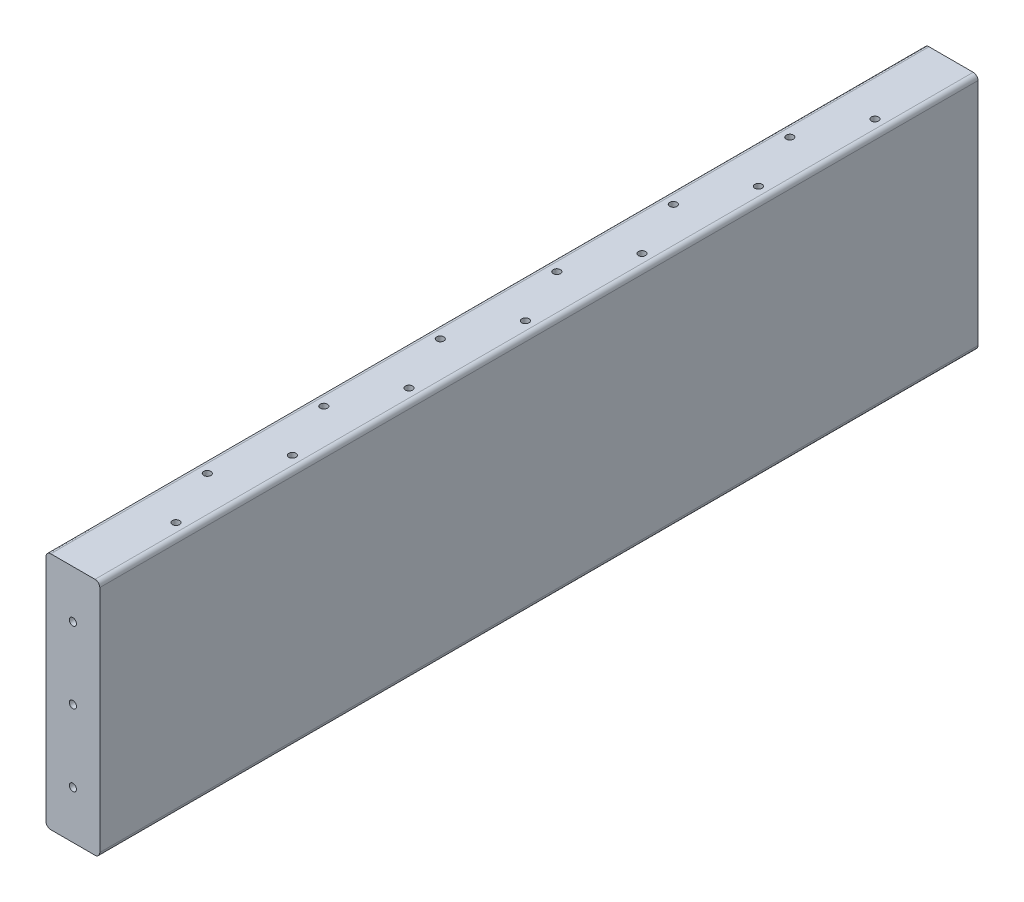
SolidWorks part; units mm, degrees
material "Beech"
ref_plane "Front Plane" through (0, 0, 0) normal (0, 0, 1) x (1, 0, 0)
ref_plane "Top Plane" through (0, 0, 0) normal (0, 1, 0) x (1, 0, 0)
ref_plane "Right Plane" through (0, 0, 0) normal (1, 0, 0) x (0, 0, -1)
sketch "Sketch1" plane through (0, 0, 0) normal (0, 0, 1) x (1, 0, 0)
  line L0 (-31.1883, 134.2727) -> (-31.1883, -65.7273)
  line L1 (-31.1883, -65.7273) -> (13.8117, -65.7273)
  line L2 (-31.1883, 134.2727) -> (13.8117, 134.2727)
  line L3 (13.8117, 134.2727) -> (13.8117, -65.7273)
extrude "Boss-Extrude1" add sketch "Sketch1" along normal blind 735
fillet "Fillet1" radius 4 4 edges at (-31.1883, -65.7273, 367.5) (13.8117, -65.7273, 367.5) (-31.1883, 134.2727, 367.5) (13.8117, 134.2727, 367.5)
hole_wizard "Ø6.0mm Dowel Slot1" positions "Sketch2" profile "Sketch3" size "Ø6.0" standard "ISO" slot yes
sketch "Sketch2" plane through (863.8117, -65.7273, 780) normal (0, 0, 1) x (1, 0, 0)
  point P0 (-872.5, 160)
  point P2 (-872.5, 100)
  point P4 (-872.5, 40)
sketch "Sketch3" plane through (-8.6883, 94.2727, 780) normal (1, 0, 0) x (0, -1, 0)
  line L0 (0, 0) -> (0, 65)
  line L1 (0, 65) -> (3, 63.1974)
  line L2 (3, 63.1974) -> (3, 0.025)
  line L3 (3, 0.025) -> (3.025, 0)
  line L4 (3.025, 0) -> (0, 0)
  line L5 (-3, 0.025) -> (-3.025, 0) construction
  line L6 (0, 65) -> (-3, 63.1974) construction
  line L7 (0, -6.35) -> (0, 107.95) construction
  dimension "Hole Dia." = 6
  dimension "Hole Depth" = 65
  dimension "Near C'Sink Dia." = 6.05
  dimension "Near C'Sink Angle" = 90
  dimension "Drill Angle" = 118
hole_wizard "Ø6.0mm Dowel Slot2" positions "Sketch4" profile "Sketch5" size "Ø6.0" standard "ISO" slot yes
sketch "Sketch4" plane through (863.8117, -65.7273, -45) normal (0, 0, -1) x (-1, 0, 0)
  point P0 (872.5, 160)
  point P2 (872.5, 100)
  point P4 (872.5, 40)
sketch "Sketch5" plane through (-8.6883, 94.2727, -45) normal (1, 0, 0) x (0, 1, 0)
  line L0 (0, 0) -> (0, 65)
  line L1 (0, 65) -> (3, 63.1974)
  line L2 (3, 63.1974) -> (3, 0.025)
  line L3 (3, 0.025) -> (3.025, 0)
  line L4 (3.025, 0) -> (0, 0)
  line L5 (-3, 0.025) -> (-3.025, 0) construction
  line L6 (0, 65) -> (-3, 63.1974) construction
  line L7 (0, -6.35) -> (0, 107.95) construction
  dimension "Hole Dia." = 6
  dimension "Hole Depth" = 65
  dimension "Near C'Sink Dia." = 6.05
  dimension "Near C'Sink Angle" = 90
  dimension "Drill Angle" = 118
hole_wizard "Ø6.0mm Dowel Slot3" [suppressed] positions "Sketch6" profile "Sketch7" size "Ø6.0" standard "ISO"
sketch "Sketch6" plane through (-971.1883, 146.2727, -45) normal (0, 1, 0) x (0, 0, 1)
  point P0 (22.5608, 973.75)
  point P3 (22.5608, 951.25)
  point P6 (802.5608, 973.75)
  point P9 (802.5608, 951.25)
  point P12 (120.3608, 951.25)
  point P16 (71.3108, 973.75)
  point P20 (169.1108, 973.75)
  point P22 (218.1608, 951.25)
  point P24 (266.9108, 973.75)
  point P26 (315.9608, 951.25)
  point P28 (364.7108, 973.75)
  point P30 (413.7608, 951.25)
  point P32 (462.5108, 973.75)
  point P34 (511.5608, 951.25)
  point P36 (560.3108, 973.75)
  point P41 (609.3608, 951.25)
  point P43 (658.1108, 973.75)
  point P45 (707.1608, 951.25)
  point P50 (755.9108, 973.75)
sketch "Sketch7" plane through (2.5617, 146.2727, -22.4392) normal (1, 0, 0) x (0, 0, 1)
  line L0 (0, 0) -> (0, 30)
  line L1 (0, 30) -> (3, 28.1974)
  line L2 (3, 28.1974) -> (3, 0)
  line L3 (3, 0) -> (0, 0)
  line L4 (0, 30) -> (-3, 28.1974) construction
  line L5 (0, -6.35) -> (0, 107.95) construction
  dimension "Hole Dia." = 6
  dimension "Hole Depth" = 30
  dimension "Drill Angle" = 118
ref_plane "Plane1" through (0, 34.2727, 0) normal (0, 1, 0) x (1, 0, 0)
mirror "Mirror1" [suppressed] about plane through (0, 34.2727, 0) normal (0, 1, 0)
hole_wizard "Ø6.0mm Dowel Slot4" positions "Sketch8" profile "Sketch9" size "Ø6.0" standard "ISO"
sketch "Sketch8" plane through (863.8117, 146.2727, -45) normal (0, 1, 0) x (0, 0, 1)
  point P0 (22.5608, -1722.5)
  point P3 (120.5996, -1722.5)
  point P7 (217.974, -1722.5)
  point P9 (314.7913, -1722.5)
  point P11 (412.5608, -1722.5)
  point P13 (510.3116, -1722.5)
  point P15 (607.5219, -1722.5)
  point P17 (704.9775, -1722.5)
  point P19 (802.5608, -1722.5)
  point P22 (802.5608, -1458.5)
  point P26 (802.5608, -1546.5)
  point P28 (802.5608, -1634.5)
  point P30 (22.5608, -1546.5)
  point P34 (22.5608, -1458.5)
  point P36 (22.5608, -1634.5)
  point P38 (22.5608, -932.5)
  point P41 (-22.4962, -917.6022)
  point P44 (71.2428, -861.25)
  point P48 (120.5996, -883.75)
  point P52 (169.2328, -861.25)
  point P54 (217.974, -883.75)
  point P56 (268.0506, -861.25)
  point P58 (314.7913, -883.75)
  point P60 (364.7201, -861.25)
  point P62 (414.2928, -883.75)
  point P64 (462.5664, -861.25)
  point P66 (511.551, -883.75)
  point P68 (560.2153, -861.25)
  point P70 (657.9263, -861.25)
  point P72 (609.5282, -883.75)
  point P74 (707.1553, -883.75)
  point P76 (755.5069, -861.25)
  point P78 (802.5608, -932.5)
  point P80 (847.4962, -917.6022)
  point P83 (927.0078, -850.8784)
  point P86 (1006.7507, -783.9604)
  point P90 (1086.3394, -717.1719)
  point P93 (802.5608, -761.25)
  point P96 (802.5608, -664.25)
  point P99 (1166.0052, -650.3187)
  point P102 (1185.001, -609.0604)
  point P105 (1185.001, -511.1051)
  point P109 (1185.001, -409.0604)
  point P112 (1185.001, -309.1708)
  point P114 (1185.001, -209.0363)
  point P116 (1185.001, -109.0604)
  point P119 (1185.001, -9.0604)
  point P122 (1021.9151, 22.5)
  point P125 (1024.5, 67.5)
  point P128 (1133.73, 67.5)
  point P131 (1133.73, 22.5)
  point P134 (913.5, 67.5)
  point P137 (910.7185, 22.5)
  point P141 (802.5, 67.5)
  point P147 (802.5, 22.5)
  point P149 (688.5, 67.5)
  point P152 (688.5, 22.5)
  point P154 (577.5192, 67.5)
  point P156 (577.9151, 22.5)
  point P159 (466.3273, 67.5)
  point P161 (466.3273, 22.5)
  point P163 (355.5, 67.5)
  point P166 (355.9151, 22.5)
  point P169 (244.5, 67.5)
  point P172 (244.5, 22.5)
  point P174 (133.5309, 67.5)
  point P176 (133.5309, 22.5)
  point P178 (22.5608, 67.5)
  point P180 (22.5608, 22.5)
  point P182 (-87.7299, 67.5)
  point P184 (-88.0849, 22.5)
  point P187 (-199.0849, 67.5)
  point P190 (-199.0849, 22.5)
  point P193 (-310.0849, 22.5)
  point P196 (-310.0849, 67.5)
  point P199 (-341.0052, -650.3187)
  point P202 (-261.3394, -717.1719)
  point P205 (-181.7507, -783.9604)
  point P209 (-102.0078, -850.8784)
  point P211 (22.5608, -77.5)
  point P214 (22.5608, -179.25)
  point P217 (22.5608, -275.9132)
  point P219 (22.5608, -373.0681)
  point P221 (22.5608, -469.6127)
  point P223 (22.5608, -567.3178)
  point P225 (22.5608, -664.25)
  point P228 (22.5608, -761.25)
  point P231 (802.5608, 167.5)
  point P234 (1185.001, 190.9134)
  point P236 (1185.001, 90.9396)
  point P239 (1185.001, 290.9396)
  point P242 (1185.001, 390.9396)
  point P245 (1185.001, 491.2681)
  point P247 (1185.001, 590.9396)
  point P250 (1185.001, 699.7184)
  point P253 (1166.0052, 740.3187)
  point P256 (1086.3394, 807.1719)
  point P259 (1006.7507, 873.9604)
  point P263 (927.0078, 940.8784)
  point P266 (847.4962, 1007.6022)
  point P269 (802.5608, 1022.8195)
  point P271 (802.5608, 973.75)
  point P274 (802.5608, 951.25)
  point P277 (755.5069, 973.75)
  point P281 (802.5608, 852.5)
  point P284 (707.1553, 951.25)
  point P288 (657.9263, 973.75)
  point P290 (609.5282, 951.25)
  point P292 (560.2153, 973.75)
  point P294 (511.5608, 951.25)
  point P297 (462.5664, 973.75)
  point P299 (412.5608, 951.25)
  point P301 (364.7108, 973.75)
  point P304 (315.9608, 951.25)
  point P307 (266.9108, 973.75)
  point P310 (218.1608, 951.25)
  point P313 (169.1108, 973.75)
  point P316 (120.3608, 951.25)
  point P319 (71.3108, 973.75)
  point P322 (22.5608, 973.75)
  point P325 (22.5608, 1022.5)
  point P328 (22.5608, 951.25)
  point P331 (-102.0078, 940.8784)
  point P334 (-181.7507, 873.9604)
  point P338 (-22.4962, 1007.6022)
  point P341 (-261.3394, 807.1719)
  point P343 (-341.0052, 740.3187)
  point P346 (-360, 699.5681)
  point P349 (-360, 590.9396)
  point P353 (-360, 491.2681)
  point P355 (-360, 390.9396)
  point P357 (-360, 290.9396)
  point P359 (-360, 190.9134)
  point P361 (-360, 90.9396)
  point P363 (-360, -11.9775)
  point P365 (-360, -77.5)
  point P367 (-360, -179.25)
  point P369 (-360, -275.9132)
  point P371 (-360, -373.0681)
  point P373 (-360, -469.6127)
  point P375 (-360, -609.5213)
  point P378 (22.5608, 1812.5)
  point P381 (71.3108, 1812.5)
  point P383 (120.3608, 1812.5)
  point P385 (169.1108, 1812.5)
  point P387 (218.1608, 1812.5)
  point P389 (266.9108, 1812.5)
  point P391 (315.9608, 1812.5)
  point P393 (364.7108, 1812.5)
  point P395 (412.5608, 1812.5)
  point P397 (462.5664, 1812.5)
  point P399 (511.5608, 1812.5)
  point P401 (577.5192, 1812.5)
  point P403 (657.9263, 1812.5)
  point P405 (755.5069, 1812.5)
  point P407 (22.5, 1724.66)
  point P410 (22.5608, 1636.4608)
  point P412 (802.5608, 1812.5)
  point P415 (802.5, 1724.66)
  point P418 (802.5608, 1636.4608)
  point P420 (802.5608, 1548.5146)
  point P432 (22.5608, 851.2226)
  point P434 (22.5608, 754.3426)
  point P436 (22.5608, 657.4768)
  point P438 (22.5608, 559.5838)
  point P440 (22.5608, 463.0035)
  point P442 (22.5608, 365.956)
  point P444 (22.5608, 269.1268)
  point P446 (22.5608, 167.5)
sketch "Sketch9" plane through (-858.6883, 146.2727, -22.4392) normal (1, 0, 0) x (0, 0, 1)
  line L0 (0, 0) -> (0, 30)
  line L1 (0, 30) -> (3, 28.1974)
  line L2 (3, 28.1974) -> (3, 0.025)
  line L3 (3, 0.025) -> (3.025, 0)
  line L4 (3.025, 0) -> (0, 0)
  line L5 (-3, 0.025) -> (-3.025, 0) construction
  line L6 (0, 30) -> (-3, 28.1974) construction
  line L7 (0, -6.35) -> (0, 107.95) construction
  dimension "Hole Dia." = 6
  dimension "Hole Depth" = 30
  dimension "Near C'Sink Dia." = 6.05
  dimension "Near C'Sink Angle" = 90
  dimension "Drill Angle" = 118
hole_wizard "Ø6.0mm Dowel Slot5" positions "Sketch10" profile "Sketch11" size "Ø6.0" standard "ISO"
sketch "Sketch10" plane through (-971.1883, 146.2727, -45) normal (0, 1, 0) x (0, 0, 1)
  point P0 (22.5608, -1722.5)
  point P3 (120.5996, -1722.5)
  point P7 (217.974, -1722.5)
  point P9 (314.7913, -1722.5)
  point P11 (412.5608, -1722.5)
  point P13 (510.3116, -1722.5)
  point P15 (607.5219, -1722.5)
  point P17 (704.9775, -1722.5)
  point P19 (802.5608, -1722.5)
  point P22 (802.5608, -1458.5)
  point P26 (802.5608, -1546.5)
  point P28 (802.5608, -1634.5)
  point P30 (22.5608, -1546.5)
  point P34 (22.5608, -1458.5)
  point P36 (22.5608, -1634.5)
  point P38 (22.5608, -932.5)
  point P41 (-22.4962, -917.6022)
  point P44 (71.2428, -861.25)
  point P48 (120.5996, -883.75)
  point P52 (169.2328, -861.25)
  point P54 (217.974, -883.75)
  point P56 (268.0506, -861.25)
  point P58 (314.7913, -883.75)
  point P60 (364.7201, -861.25)
  point P62 (414.2928, -883.75)
  point P64 (462.5664, -861.25)
  point P66 (511.551, -883.75)
  point P68 (560.2153, -861.25)
  point P70 (657.9263, -861.25)
  point P72 (609.5282, -883.75)
  point P74 (707.1553, -883.75)
  point P76 (755.5069, -861.25)
  point P78 (802.5608, -932.5)
  point P80 (847.4962, -917.6022)
  point P83 (927.0078, -850.8784)
  point P86 (1006.7507, -783.9604)
  point P90 (1086.3394, -717.1719)
  point P93 (802.5608, -761.25)
  point P96 (802.5608, -664.25)
  point P99 (1166.0052, -650.3187)
  point P102 (1185.001, -609.0604)
  point P105 (1185.001, -511.1051)
  point P109 (1185.001, -409.0604)
  point P112 (1185.001, -309.1708)
  point P114 (1185.001, -209.0363)
  point P116 (1185.001, -109.0604)
  point P119 (1185.001, -9.0604)
  point P122 (1021.9151, 22.5)
  point P125 (1024.5, 67.5)
  point P128 (1133.73, 67.5)
  point P131 (1133.73, 22.5)
  point P134 (913.5, 67.5)
  point P137 (910.7185, 22.5)
  point P141 (802.5, 67.5)
  point P147 (802.5, 22.5)
  point P149 (688.5, 67.5)
  point P152 (688.5, 22.5)
  point P154 (577.5192, 67.5)
  point P156 (577.9151, 22.5)
  point P159 (466.3273, 67.5)
  point P161 (466.3273, 22.5)
  point P163 (355.5, 67.5)
  point P166 (355.9151, 22.5)
  point P169 (244.5, 67.5)
  point P172 (244.5, 22.5)
  point P174 (133.5309, 67.5)
  point P176 (133.5309, 22.5)
  point P178 (22.5608, 67.5)
  point P180 (22.5608, 22.5)
  point P182 (-87.7299, 67.5)
  point P184 (-88.0849, 22.5)
  point P187 (-199.0849, 67.5)
  point P190 (-199.0849, 22.5)
  point P193 (-310.0849, 22.5)
  point P196 (-310.0849, 67.5)
  point P199 (-341.0052, -650.3187)
  point P202 (-261.3394, -717.1719)
  point P205 (-181.7507, -783.9604)
  point P209 (-102.0078, -850.8784)
  point P211 (22.5608, -77.5)
  point P214 (22.5608, -179.25)
  point P217 (22.5608, -275.9132)
  point P219 (22.5608, -373.0681)
  point P221 (22.5608, -469.6127)
  point P223 (22.5608, -567.3178)
  point P225 (22.5608, -664.25)
  point P228 (22.5608, -761.25)
  point P231 (802.5608, 167.5)
  point P234 (1185.001, 190.9134)
  point P236 (1185.001, 90.9396)
  point P239 (1185.001, 290.9396)
  point P242 (1185.001, 390.9396)
  point P245 (1185.001, 491.2681)
  point P247 (1185.001, 590.9396)
  point P250 (1185.001, 699.7184)
  point P253 (1166.0052, 740.3187)
  point P256 (1086.3394, 807.1719)
  point P259 (1006.7507, 873.9604)
  point P263 (927.0078, 940.8784)
  point P266 (847.4962, 1007.6022)
  point P269 (802.5608, 1022.8195)
  point P271 (802.5608, 973.75)
  point P274 (802.5608, 951.25)
  point P277 (755.5069, 973.75)
  point P281 (802.5608, 852.5)
  point P284 (707.1553, 951.25)
  point P288 (657.9263, 973.75)
  point P290 (609.5282, 951.25)
  point P292 (560.2153, 973.75)
  point P294 (511.5608, 951.25)
  point P297 (462.5664, 973.75)
  point P299 (412.5608, 951.25)
  point P301 (364.7108, 973.75)
  point P304 (315.9608, 951.25)
  point P307 (266.9108, 973.75)
  point P310 (218.1608, 951.25)
  point P313 (169.1108, 973.75)
  point P316 (120.3608, 951.25)
  point P319 (71.3108, 973.75)
  point P322 (22.5608, 973.75)
  point P325 (22.5608, 1022.5)
  point P328 (22.5608, 951.25)
  point P331 (-102.0078, 940.8784)
  point P334 (-181.7507, 873.9604)
  point P338 (-22.4962, 1007.6022)
  point P341 (-261.3394, 807.1719)
  point P343 (-341.0052, 740.3187)
  point P346 (-360, 699.5681)
  point P349 (-360, 590.9396)
  point P353 (-360, 491.2681)
  point P355 (-360, 390.9396)
  point P357 (-360, 290.9396)
  point P359 (-360, 190.9134)
  point P361 (-360, 90.9396)
  point P363 (-360, -11.9775)
  point P365 (-360, -77.5)
  point P367 (-360, -179.25)
  point P369 (-360, -275.9132)
  point P371 (-360, -373.0681)
  point P373 (-360, -469.6127)
  point P375 (-360, -609.5213)
  point P378 (22.5608, 1812.5)
  point P381 (71.3108, 1812.5)
  point P383 (120.3608, 1812.5)
  point P385 (169.1108, 1812.5)
  point P387 (218.1608, 1812.5)
  point P389 (266.9108, 1812.5)
  point P391 (315.9608, 1812.5)
  point P393 (364.7108, 1812.5)
  point P395 (412.5608, 1812.5)
  point P397 (462.5664, 1812.5)
  point P399 (511.5608, 1812.5)
  point P401 (577.5192, 1812.5)
  point P403 (657.9263, 1812.5)
  point P405 (755.5069, 1812.5)
  point P407 (22.5, 1724.66)
  point P410 (22.5608, 1636.4608)
  point P412 (802.5608, 1812.5)
  point P415 (802.5, 1724.66)
  point P418 (802.5608, 1636.4608)
  point P420 (802.5608, 1548.5146)
  point P432 (22.5608, 851.2226)
  point P434 (22.5608, 754.3426)
  point P436 (22.5608, 657.4768)
  point P438 (22.5608, 559.5838)
  point P440 (22.5608, 463.0035)
  point P442 (22.5608, 365.956)
  point P444 (22.5608, 269.1268)
  point P446 (22.5608, 167.5)
sketch "Sketch11" plane through (-2693.6883, 146.2727, -22.4392) normal (1, 0, 0) x (0, 0, 1)
  line L0 (0, 0) -> (0, 30)
  line L1 (0, 30) -> (3, 28.1974)
  line L2 (3, 28.1974) -> (3, 0.025)
  line L3 (3, 0.025) -> (3.025, 0)
  line L4 (3.025, 0) -> (0, 0)
  line L5 (-3, 0.025) -> (-3.025, 0) construction
  line L6 (0, 30) -> (-3, 28.1974) construction
  line L7 (0, -6.35) -> (0, 107.95) construction
  dimension "Hole Dia." = 6
  dimension "Hole Depth" = 30
  dimension "Near C'Sink Dia." = 6.05
  dimension "Near C'Sink Angle" = 90
  dimension "Drill Angle" = 118
hole_wizard "Ø6.0mm Dowel Slot6" positions "Sketch12" profile "Sketch13" size "Ø6.0" standard "ISO" slot yes
sketch "Sketch12" plane through (863.8117, 146.2727, -45) normal (0, 1, 0) x (0, 0, 1)
  line L17 (802.5, 1812.5) -> (22.5, 1812.5)
  line L18 (-360, 699.4255) -> (-360, -609.5213)
  line L23 (1185.001, 699.4255) -> (1185, -609.5213)
  point P0 (22.5, 1726.5)
  point P4 (22.5, 1640.5)
  point P6 (802.5, 1726.5)
  point P10 (802.5, 1640.5)
  point P12 (22.5, -955.9606)
  point P14 (22.5, -1636.5)
  point P16 (802.5, -1462.5)
  point P18 (802.5, -1636.5)
  point P19 (22.5, -1722.5)
  point P22 (802.5, -1722.5)
  point P25 (22.5, -1550.5)
  point P27 (802.5, -640.31)
  point P33 (120, -1722.5)
  point P37 (217.5, -1722.5)
  point P39 (315, -1722.5)
  point P41 (412.5, -1722.5)
  point P43 (510, -1722.5)
  point P45 (607.5, -1722.5)
  point P48 (705, -1722.5)
  point P51 (22.5, -861.25)
  point P54 (22.5, -883.75)
  point P57 (-22.4962, -917.6022)
  point P60 (802.5, -861.25)
  point P63 (802.5, -883.75)
  point P66 (847.4962, -917.6022)
  point P69 (802.5, -529.84)
  point P71 (22.5, -750.2496)
  point P73 (-341.0052, -650.3187)
  point P76 (1166.0052, -650.3187)
  point P85 (-310.0849, 22.5)
  point P88 (-310.0849, 67.5)
  point P91 (22.5, 67.5)
  point P95 (22.5, 22.5)
  point P99 (802.5, 67.5)
  point P101 (802.5, 22.5)
  point P103 (1133.73, 67.5)
  point P106 (1133.73, 22.5)
  point P112 (1166.0052, 740.3187)
  point P115 (802.5608, 973.75)
  point P118 (802.5608, 951.25)
  point P121 (847.4962, 1007.6022)
  point P124 (-22.4962, 1007.6022)
  point P127 (22.5608, 951.25)
  point P130 (22.5608, 951.25)
  point P133 (-341.0052, 740.3187)
  point P139 (22.5, 1812.5)
  point P142 (802.5, 1812.5)
  point P148 (22.5, 1552.5)
  point P150 (802.5, 1552.5)
  point P160 (-102.162, -850.749)
  point P164 (-181.8278, -783.8957)
  point P166 (-261.4937, -717.0425)
  point P168 (927.162, -850.749)
  point P172 (1006.8278, -783.8957)
  point P174 (1086.4937, -717.0425)
  point P176 (1086.4937, 807.0425)
  point P180 (1006.8278, 873.8957)
  point P182 (927.162, 940.749)
  point P184 (-102.162, 940.749)
  point P188 (-181.8278, 873.8957)
  point P190 (-261.4937, 807.0425)
  point P193 (-199.2249, 67.5)
  point P195 (-88.3649, 67.5)
  point P197 (-199.2249, 22.5)
  point P199 (-88.3649, 22.5)
  point P201 (912.01, 67.5)
  point P203 (1022.87, 67.5)
  point P205 (912.01, 22.5)
  point P207 (1022.87, 22.5)
  point P268 (120, 67.5)
  point P270 (217.5, 67.5)
  point P272 (315, 67.5)
  point P276 (607.5, 67.5)
  point P278 (705, 67.5)
  point P283 (510, 67.5)
  point P292 (120, 22.5)
  point P294 (217.5, 22.5)
  point P296 (315, 22.5)
  point P300 (510, 22.5)
  point P302 (607.5, 22.5)
  point P304 (705, 22.5)
  point P307 (412.5, 22.5)
  point P309 (22.5, -750.78)
  point P311 (22.5, -640.31)
  point P313 (22.5, -529.84)
  point P315 (22.5, -419.37)
  point P317 (22.5, -308.9)
  point P319 (22.5, -198.43)
  point P321 (22.5, -87.96)
  point P324 (802.5, -750.78)
  point P326 (802.5, -419.37)
  point P330 (802.5, -308.9)
  point P336 (802.5, -198.43)
  point P337 (22.5, 177.97)
  point P339 (22.5, 288.44)
  point P341 (22.5, 398.91)
  point P343 (22.5, 509.38)
  point P345 (22.5, 619.85)
  point P347 (22.5, 730.32)
  point P349 (22.5, 840.79)
  point P352 (802.5, -87.96)
  point P360 (802.5, 177.97)
  point P362 (802.5, 288.44)
  point P365 (120.0003, 1812.7537)
  point P369 (217.5, 1812.5)
  point P373 (315, 1812.5)
  point P375 (412.5, 1812.5)
  point P377 (510, 1812.5)
  point P379 (607.5, 1812.5)
  point P381 (705, 1812.5)
  point P386 (120.0608, 951.25)
  point P390 (217.5608, 951.25)
  point P392 (315.0608, 951.25)
  point P397 (412.5608, 951.25)
  point P399 (510.0608, 951.25)
  point P401 (607.5608, 951.25)
  point P404 (705.0608, 951.25)
  point P406 (656.3108, 973.75)
  point P410 (558.8108, 973.75)
  point P412 (461.3108, 973.75)
  point P414 (363.8108, 973.75)
  point P421 (266.3108, 973.75)
  point P423 (168.8108, 973.75)
  point P426 (120, -861.25)
  point P430 (217.5, -861.25)
  point P432 (315, -861.25)
  point P434 (412.5, -861.25)
  point P436 (510, -861.25)
  point P438 (607.5, -861.25)
  point P440 (705, -861.25)
  point P446 (656.25, -883.75)
  point P450 (558.75, -883.75)
  point P452 (461.25, -883.75)
  point P454 (168.75, -883.75)
  point P456 (266.25, -883.75)
  point P458 (363.75, -883.75)
  point P460 (802.5608, -955.9606)
  point P465 (412.5, 67.5)
  point P509 (802.5, 730.32)
  point P511 (802.5608, 840.79)
  point P517 (802.5, 398.91)
  point P523 (802.5, 509.38)
  point P525 (802.5, 619.85)
  point P528 (-360, 699.4255)
  point P529 (-360, -609.5213)
  point P549 (-360, 598.7255)
  point P551 (-360, 498.0255)
  point P555 (-360, 397.3255)
  point P557 (-360, 296.6255)
  point P559 (-360, 195.9255)
  point P561 (-360, 95.2255)
  point P563 (-360, -5.4745)
  point P568 (-360, -106.1745)
  point P570 (-360, -206.8745)
  point P572 (-360, -307.5745)
  point P574 (-360, -408.2745)
  point P576 (-360, -508.9745)
  point P586 (1185.001, 699.4255)
  point P596 (1185.0009, 598.7255)
  point P598 (1185.0009, 498.0255)
  point P605 (1185.0007, 296.6255)
  point P607 (1185.0006, 195.9255)
  point P609 (1185.0006, 95.2255)
  point P611 (1185.0005, -5.4745)
  point P613 (1185.0004, -106.1745)
  point P615 (1185.0003, -206.8745)
  point P617 (1185.0002, -408.2745)
  point P619 (1185.0001, -508.9745)
  point P622 (1185.0008, 397.3255)
  point P625 (22.5608, 1016.3858)
  point P627 (802.5608, 1016.3858)
  point P628 (802.5608, -1550.5)
  point P630 (22.5608, 973.75)
  point P633 (802.5608, -363.9667)
sketch "Sketch13" plane through (2590.3117, 146.2727, -22.5) normal (1, 0, 0) x (0, 0, 1)
  line L0 (0, 0) -> (0, 30)
  line L1 (0, 30) -> (3, 28.1974)
  line L2 (3, 28.1974) -> (3, 0.025)
  line L3 (3, 0.025) -> (3.025, 0)
  line L4 (3.025, 0) -> (0, 0)
  line L5 (-3, 0.025) -> (-3.025, 0) construction
  line L6 (0, 30) -> (-3, 28.1974) construction
  line L7 (0, -6.35) -> (0, 107.95) construction
  dimension "Hole Dia." = 6
  dimension "Hole Depth" = 30
  dimension "Near C'Sink Dia." = 6.05
  dimension "Near C'Sink Angle" = 90
  dimension "Drill Angle" = 118
hole_wizard "Ø6.0mm Dowel Slot7" [suppressed] positions "Sketch14" profile "Sketch15" size "Ø6.0" standard "ISO"
sketch "Sketch14" plane through (-971.1883, 146.2727, -45) normal (0, 1, 0) x (0, 0, 1)
  point P0 (22.5, 1726.5)
  point P4 (22.5, 1640.5)
  point P6 (802.5, 1726.5)
  point P10 (802.5, 1640.5)
  point P12 (22.5, -955.9606)
  point P14 (22.5, -1636.5)
  point P16 (802.5, -1462.5)
  point P18 (802.5, -1636.5)
  point P19 (22.5, -1722.5)
  point P22 (802.5, -1722.5)
  point P25 (22.5, -1550.5)
  point P27 (802.5, -778.9107)
  point P33 (120, -1722.5)
  point P37 (217.5, -1722.5)
  point P39 (315, -1722.5)
  point P41 (412.5, -1722.5)
  point P43 (510, -1722.5)
  point P45 (607.5, -1722.5)
  point P48 (705, -1722.5)
  point P51 (22.5, -861.25)
  point P54 (22.5, -883.75)
  point P57 (-22.4962, -917.6022)
  point P60 (802.5, -861.25)
  point P63 (802.5, -883.75)
  point P66 (847.4962, -917.6022)
  point P69 (802.5, -536.8366)
  point P71 (22.5, -750.2496)
  point P73 (-341.0052, -650.3187)
  point P76 (1166.0052, -650.3187)
  point P79 (2543.5014, 245.8654)
  point P82 (-501.5002, -524.8138)
  point P85 (-310.0849, -433.3306)
  point P88 (-310.0849, -388.3306)
  point P91 (22.5, -388.3306)
  point P95 (22.5, -433.3306)
  point P99 (802.5, -388.3306)
  point P101 (802.5, -433.3306)
  point P103 (1133.73, -388.3306)
  point P106 (1133.73, -433.3306)
  point P109 (2543.5014, -171.034)
  point P112 (1166.0052, 740.3187)
  point P115 (802.5608, 951.25)
  point P118 (802.5608, 951.25)
  point P121 (847.4962, 1007.6022)
  point P124 (-22.4962, 1007.6022)
  point P127 (22.5608, 951.25)
  point P130 (22.5608, 951.25)
  point P133 (-341.0052, 740.3187)
  point P136 (-501.5002, 393.1551)
  point P139 (22.5, 1812.5)
  point P142 (802.5, 1812.5)
  point P148 (22.5, 1552.5)
  point P150 (802.5, 1552.5)
  point P155 (22.5, 83.8102)
  point P157 (802.5, 297.2232)
  point P160 (-102.162, -850.749)
  point P164 (-181.8278, -783.8957)
  point P166 (-261.4937, -717.0425)
  point P168 (927.162, -850.749)
  point P172 (1006.8278, -783.8957)
  point P174 (1086.4937, -717.0425)
  point P176 (1086.4937, 807.0425)
  point P180 (1006.8278, 873.8957)
  point P182 (927.162, 940.749)
  point P184 (-102.162, 940.749)
  point P188 (-181.8278, 873.8957)
  point P190 (-261.4937, 807.0425)
  point P193 (-199.2249, -388.3306)
  point P195 (-88.3649, -388.3306)
  point P197 (-199.2249, -433.3306)
  point P199 (-88.3649, -433.3306)
  point P201 (912.01, -388.3306)
  point P203 (1022.87, -388.3306)
  point P205 (912.01, -433.3306)
  point P207 (1022.87, -433.3306)
  point P209 (-501.5002, -424.1138)
  point P213 (-501.5002, -323.4138)
  point P217 (-501.5002, -222.7138)
  point P219 (-501.5002, -307.2046)
  point P221 (-501.5002, -122.0138)
  point P223 (-501.5002, -21.3138)
  point P225 (-501.5002, 79.3862)
  point P227 (-501.5002, 180.0862)
  point P229 (-501.5002, 280.7862)
  point P231 (-501.5002, 381.4862)
  point P237 (-501.5002, 482.1862)
  point P239 (-501.5002, 582.8862)
  point P241 (-501.5002, 683.5862)
  point P242 (2543.5014, 145.1654)
  point P246 (2543.5014, 44.4654)
  point P248 (2543.5014, -56.2346)
  point P250 (2543.5014, -156.9346)
  point P252 (2543.5014, -257.6346)
  point P254 (2543.5014, -358.3346)
  point P256 (2543.5014, -459.0346)
  point P258 (2543.5014, -559.7346)
  point P260 (2543.5014, -660.4346)
  point P262 (2543.5014, -761.1346)
  point P264 (2543.5014, -861.8346)
  point P266 (2543.5014, -962.5346)
  point P268 (120, -388.3306)
  point P270 (217.5, -388.3306)
  point P272 (315, -388.3306)
  point P274 (592.3435, -336.1213)
  point P276 (607.5, -388.3306)
  point P278 (705, -388.3306)
  point P283 (510, -388.3306)
  point P292 (120, -433.3306)
  point P294 (217.5, -433.3306)
  point P296 (315, -433.3306)
  point P300 (510, -433.3306)
  point P302 (607.5, -433.3306)
  point P304 (705, -433.3306)
  point P307 (412.5, -433.3306)
  point P309 (22.5, -750.78)
  point P311 (22.5, -640.31)
  point P313 (22.5, -529.84)
  point P315 (22.5, -419.37)
  point P317 (22.5, -308.9)
  point P319 (22.5, -198.43)
  point P321 (22.5, -87.96)
  point P324 (802.5, -750.78)
  point P326 (802.5, -402.8046)
  point P328 (802.5, -357.1566)
  point P330 (802.5, -311.5085)
  point P332 (802.5, -265.8604)
  point P334 (802.5, -220.2123)
  point P336 (802.5, -174.5642)
  point P337 (22.5, -277.8606)
  point P339 (22.5, -167.3906)
  point P341 (22.5, -56.9206)
  point P343 (22.5, 53.5494)
  point P345 (22.5, 164.0194)
  point P347 (22.5, 274.4894)
  point P349 (22.5, 384.9594)
  point P352 (802.5, -64.6773)
  point P354 (802.5, -19.0293)
  point P356 (802.5, 72.2669)
  point P358 (802.5, 26.2178)
  point P360 (802.5, 117.915)
  point P362 (802.5, 228.385)
  point P364 (802.5, 209.2112)
  point P365 (1224.4002, 2039.7886)
  point P369 (1161.3433, 1965.4241)
  point P373 (1089.7554, 1899.2318)
  point P375 (1008.8996, 1844.747)
  point P377 (920.7821, 1803.0151)
  point P379 (823.4819, 1796.7769)
  point P381 (755.0534, 1727.3233)
  point P386 (120.0608, 951.25)
  point P390 (217.5608, 951.25)
  point P392 (315.0608, 951.25)
  point P397 (412.5608, 951.25)
  point P399 (510.0608, 951.25)
  point P401 (607.5608, 951.25)
  point P404 (705.0608, 951.25)
  point P406 (656.3108, 951.25)
  point P410 (558.8108, 951.25)
  point P412 (461.3108, 951.25)
  point P414 (363.8108, 951.25)
  point P421 (266.3108, 951.25)
  point P423 (168.8108, 951.25)
  point P426 (120, -861.25)
  point P430 (217.5, -861.25)
  point P432 (315, -861.25)
  point P434 (412.5, -861.25)
  point P436 (510, -861.25)
  point P438 (607.5, -861.25)
  point P440 (705, -861.25)
  point P446 (656.25, -883.75)
  point P450 (558.75, -883.75)
  point P452 (461.25, -883.75)
  point P454 (168.75, -883.75)
  point P456 (266.25, -883.75)
  point P458 (363.75, -883.75)
sketch "Sketch15" plane through (755.3117, 146.2727, -22.5) normal (1, 0, 0) x (0, 0, 1)
  line L0 (0, 0) -> (0, 30)
  line L1 (0, 30) -> (3, 28.1974)
  line L2 (3, 28.1974) -> (3, 0.025)
  line L3 (3, 0.025) -> (3.025, 0)
  line L4 (3.025, 0) -> (0, 0)
  line L5 (-3, 0.025) -> (-3.025, 0) construction
  line L6 (0, 30) -> (-3, 28.1974) construction
  line L7 (0, -6.35) -> (0, 107.95) construction
  dimension "Hole Dia." = 6
  dimension "Hole Depth" = 30
  dimension "Near C'Sink Dia." = 6.05
  dimension "Near C'Sink Angle" = 90
  dimension "Drill Angle" = 118
mirror "Mirror2" [suppressed]
